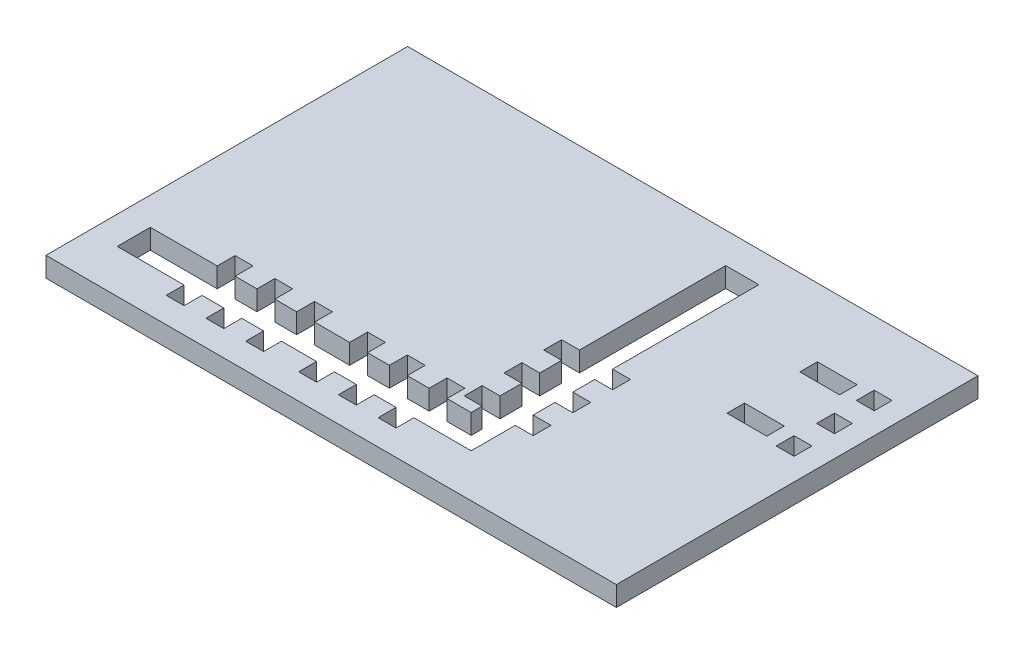
SolidWorks part; units mm, degrees
ref_plane "Front Plane" through (0, 0, 0) normal (0, 0, 1) x (1, 0, 0)
ref_plane "Top Plane" through (0, 0, 0) normal (0, 1, 0) x (1, 0, 0)
ref_plane "Right Plane" through (0, 0, 0) normal (1, 0, 0) x (0, 0, -1)
sketch "Sketch1" plane through (0, 0, 0) normal (0, 1, 0) x (1, 0, 0)
  line L1348 (192.4847, -54.0859) -> (192.4847, -56.7859)
  line L1421 (195.1847, -56.7859) -> (192.4847, -56.7859)
  line L1430 (195.1847, -54.0859) -> (195.1847, -56.7859)
  line L1431 (192.5838, -50.7859) -> (192.5838, -48.0859)
  line L1432 (195.2838, -48.0859) -> (192.5838, -48.0859)
  line L1433 (195.2838, -50.7859) -> (195.2838, -48.0859)
  line L1434 (195.2838, -50.7859) -> (192.5838, -50.7859)
  line L1435 (192.5838, -42.0859) -> (192.5838, -44.7859)
  line L1436 (195.2838, -44.7859) -> (192.5838, -44.7859)
  line L1437 (195.2838, -42.0859) -> (195.2838, -44.7859)
  line L1438 (184.4847, -53.5609) -> (184.4847, -56.2109)
  line L1439 (190.4847, -56.2109) -> (184.4847, -56.2109)
  line L1440 (190.4847, -53.5609) -> (190.4847, -56.2109)
  line L1441 (190.4847, -53.5609) -> (184.4847, -53.5609)
  line L1442 (195.2838, -42.0859) -> (192.5838, -42.0859)
  line L1443 (195.1847, -54.0859) -> (192.4847, -54.0859)
  line L1444 (184.5838, -42.6609) -> (184.5838, -45.3109)
  line L1445 (190.5838, -45.3109) -> (184.5838, -45.3109)
  line L1446 (190.5838, -42.6609) -> (190.5838, -45.3109)
  line L1447 (190.5838, -42.6609) -> (184.5838, -42.6609)
  line L1448 (129.4338, -75.4359) -> (132.7338, -75.4359)
  line L1449 (126.7338, -72.7359) -> (126.7338, -75.4359)
  line L1451 (129.4338, -72.7359) -> (129.4338, -75.4359)
  line L1452 (129.4338, -72.7359) -> (126.7338, -72.7359)
  line L1453 (132.7338, -72.7359) -> (132.7338, -75.4359)
  line L1455 (135.4338, -72.7359) -> (135.4338, -75.4359)
  line L1456 (135.4338, -72.7359) -> (132.7338, -72.7359)
  line L1457 (138.7338, -72.7359) -> (138.7338, -75.4359)
  line L1459 (141.4338, -72.7359) -> (141.4338, -75.4359)
  line L1460 (141.4338, -72.7359) -> (138.7338, -72.7359)
  line L1461 (155.4338, -80.4359) -> (155.4338, -83.1359)
  line L1462 (155.4338, -83.1359) -> (152.7338, -83.1359)
  line L1463 (152.7338, -80.4359) -> (152.7338, -83.1359)
  line L1465 (161.4338, -80.4359) -> (161.4338, -83.1359)
  line L1467 (158.7338, -80.4359) -> (158.7338, -83.1359)
  line L1468 (158.7338, -83.1359) -> (161.4338, -83.1359)
  line L1470 (158.7338, -75.4359) -> (158.7338, -72.7359)
  line L1471 (158.7338, -72.7359) -> (161.4338, -72.7359)
  line L1472 (161.4338, -75.4359) -> (161.4338, -72.7359)
  line L1473 (152.7338, -75.4359) -> (152.7338, -72.7359)
  line L1475 (155.4338, -75.4359) -> (155.4338, -72.7359)
  line L1476 (155.4338, -72.7359) -> (152.7338, -72.7359)
  line L1477 (162.3838, -67.7859) -> (165.0838, -67.7859)
  line L1478 (162.3838, -67.7859) -> (162.3838, -65.0859)
  line L1479 (162.3838, -65.0859) -> (165.0838, -65.0859)
  line L1481 (162.3838, -71.0859) -> (162.3838, -73.7859)
  line L1482 (162.3838, -73.7859) -> (165.0838, -73.7859)
  line L1484 (162.3838, -71.0859) -> (165.0838, -71.0859)
  line L1485 (172.7838, -71.0859) -> (170.0838, -71.0859)
  line L1487 (172.7838, -73.7859) -> (170.0838, -73.7859)
  line L1488 (172.7838, -71.0859) -> (172.7838, -73.7859)
  line L1489 (172.7838, -67.7859) -> (172.7838, -65.0859)
  line L1490 (172.7838, -65.0859) -> (170.0838, -65.0859)
  line L1492 (172.7838, -67.7859) -> (170.0838, -67.7859)
  line L1493 (141.4338, -83.1359) -> (138.7338, -83.1359)
  line L1494 (141.4338, -83.1359) -> (141.4338, -80.4359)
  line L1496 (138.7338, -83.1359) -> (138.7338, -80.4359)
  line L1497 (135.4338, -83.1359) -> (132.7338, -83.1359)
  line L1498 (135.4338, -83.1359) -> (135.4338, -80.4359)
  line L1500 (132.7338, -83.1359) -> (132.7338, -80.4359)
  line L1501 (129.4338, -83.1359) -> (126.7338, -83.1359)
  line L1502 (129.4338, -83.1359) -> (129.4338, -80.4359)
  line L1504 (126.7338, -83.1359) -> (126.7338, -80.4359)
  line L1505 (149.4338, -80.4359) -> (149.4338, -83.1359)
  line L1507 (146.7338, -80.4359) -> (146.7338, -83.1359)
  line L1508 (146.7338, -83.1359) -> (149.4338, -83.1359)
  line L1510 (146.7338, -75.4359) -> (146.7338, -72.7359)
  line L1511 (146.7338, -72.7359) -> (149.4338, -72.7359)
  line L1512 (149.4338, -75.4359) -> (149.4338, -72.7359)
  line L1513 (162.3838, -61.7859) -> (165.0838, -61.7859)
  line L1514 (162.3838, -61.7859) -> (162.3838, -59.0859)
  line L1515 (162.3838, -59.0859) -> (165.0838, -59.0859)
  line L1517 (172.7838, -61.7859) -> (172.7838, -59.0859)
  line L1518 (172.7838, -59.0859) -> (170.0838, -59.0859)
  line L1520 (172.7838, -61.7859) -> (170.0838, -61.7859)
  line L1521 (198.54, -32.3667) -> (112.4195, -32.3667)
  line L1522 (116.6351, -75.4359) -> (126.7338, -75.4359)
  line L1523 (116.6351, -75.4359) -> (116.6351, -80.4359)
  line L1524 (116.6351, -80.4359) -> (126.7338, -80.4359)
  line L1525 (170.0838, -75.4359) -> (170.0838, -80.4359)
  line L1527 (170.0838, -75.4359) -> (170.0838, -73.7859)
  line L1528 (170.0838, -37.002) -> (165.0838, -37.002)
  line L1529 (165.0838, -75.4359) -> (165.0838, -73.7859)
  line L1530 (198.54, -32.3667) -> (198.54, -86.9753)
  line L1531 (198.54, -86.9753) -> (112.4195, -86.9753)
  line L1532 (112.4195, -32.3667) -> (112.4195, -86.9753)
  line L1533 (129.4338, -80.4359) -> (132.7338, -80.4359)
  line L1534 (135.4338, -75.4359) -> (138.7338, -75.4359)
  line L1535 (135.4338, -80.4359) -> (138.7338, -80.4359)
  line L1536 (141.4338, -80.4359) -> (146.7338, -80.4359)
  line L1537 (141.4338, -75.4359) -> (146.7338, -75.4359)
  line L1538 (149.4338, -75.4359) -> (152.7338, -75.4359)
  line L1539 (149.4338, -80.4359) -> (152.7338, -80.4359)
  line L1540 (155.4338, -75.4359) -> (158.7338, -75.4359)
  line L1541 (155.4338, -80.4359) -> (158.7338, -80.4359)
  line L1542 (161.4338, -75.4359) -> (165.0838, -75.4359)
  line L1543 (161.4338, -80.4359) -> (170.0838, -80.4359)
  line L1544 (165.0838, -71.0859) -> (165.0838, -67.7859)
  line L1545 (170.0838, -71.0859) -> (170.0838, -67.7859)
  line L1546 (165.0838, -65.0859) -> (165.0838, -61.7859)
  line L1547 (170.0838, -65.0859) -> (170.0838, -61.7859)
  line L1548 (165.0838, -59.0859) -> (165.0838, -37.002)
  line L1549 (170.0838, -59.0859) -> (170.0838, -37.002)
extrude "Boss-Extrude1" add sketch "Sketch1" along normal blind 3
